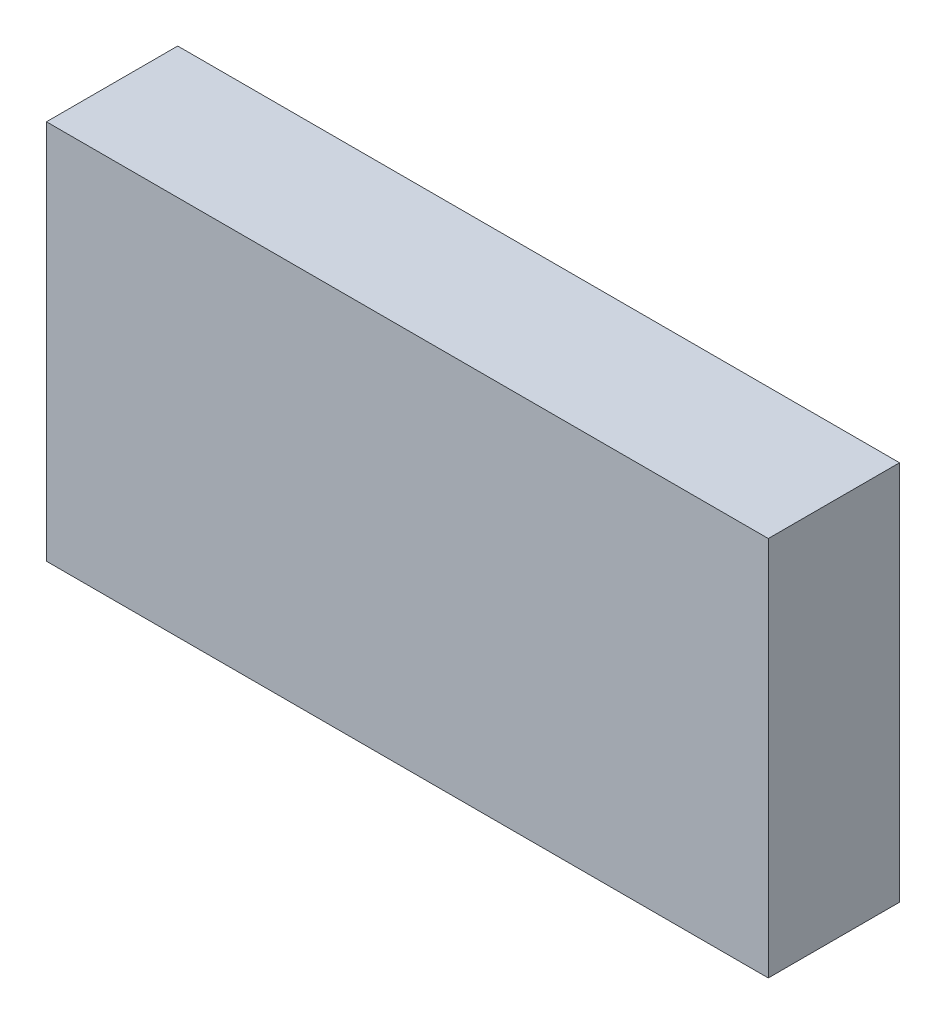
SolidWorks part; units mm, degrees
ref_plane "Plan de face" through (0, 0, 0) normal (0, 0, 1) x (1, 0, 0)
ref_plane "Plan de dessus" through (0, 0, 0) normal (0, 1, 0) x (1, 0, 0)
ref_plane "Plan de droite" through (0, 0, 0) normal (1, 0, 0) x (0, 0, -1)
sketch "Esquisse1" plane through (0, 0, 0) normal (0, 0, 1) x (1, 0, 0)
  line L1 (0, 0) -> (55, 0)
  line L2 (0, 0) -> (0, 29)
  line L3 (0, 29) -> (55, 29)
  line L4 (55, 0) -> (55, 29)
  dimension "D1" = 55
  dimension "D2" = 29
extrude "Boss.-Extru.1" add sketch "Esquisse1" along normal blind 10
